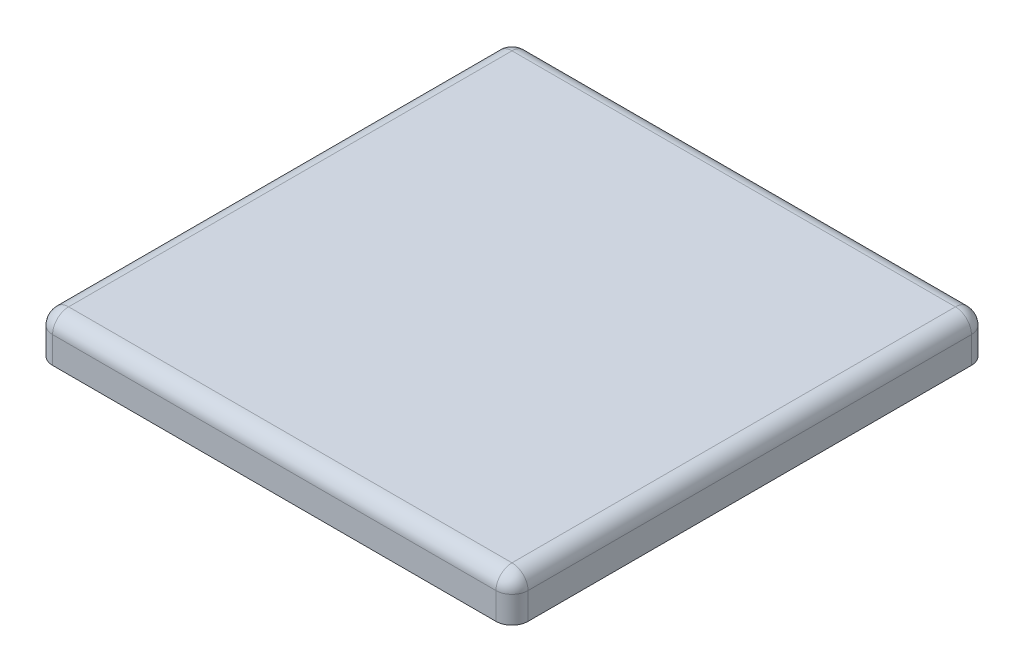
SolidWorks part; units mm, degrees
material "ABS"
ref_plane "Front Plane" through (0, 0, 0) normal (0, 0, 1) x (1, 0, 0)
ref_plane "Top Plane" through (0, 0, 0) normal (0, 1, 0) x (1, 0, 0)
ref_plane "Right Plane" through (0, 0, 0) normal (1, 0, 0) x (0, 0, -1)
sketch "Sketch1" plane through (0, 0, 0) normal (0, 1, 0) x (1, 0, 0)
  line L1 (44.5, 44.5) -> (-44.5, 44.5)
  line L2 (44.5, 44.5) -> (44.5, -44.5)
  line L3 (44.5, -44.5) -> (-44.5, -44.5)
  line L4 (-44.5, 44.5) -> (-44.5, -44.5)
  line L5 (44.5, 44.5) -> (-44.5, -44.5) construction
  line L6 (44.5, -44.5) -> (-44.5, 44.5) construction
  point P0 (0, 0)
  dimension "D1" = 89
  dimension "D2" = 89
extrude "Boss-Extrude1" add sketch "Sketch1" along normal blind 8
fillet "Fillet1" radius 3 8 edges at (0, 8, -44.5) (44.5, 8, 0) (0, 8, 44.5) (-44.5, 8, 0) (-44.5, 4, -44.5) (-44.5, 4, 44.5) (44.5, 4, -44.5) (44.5, 4, 44.5)
shell "Shell1" thickness 2
